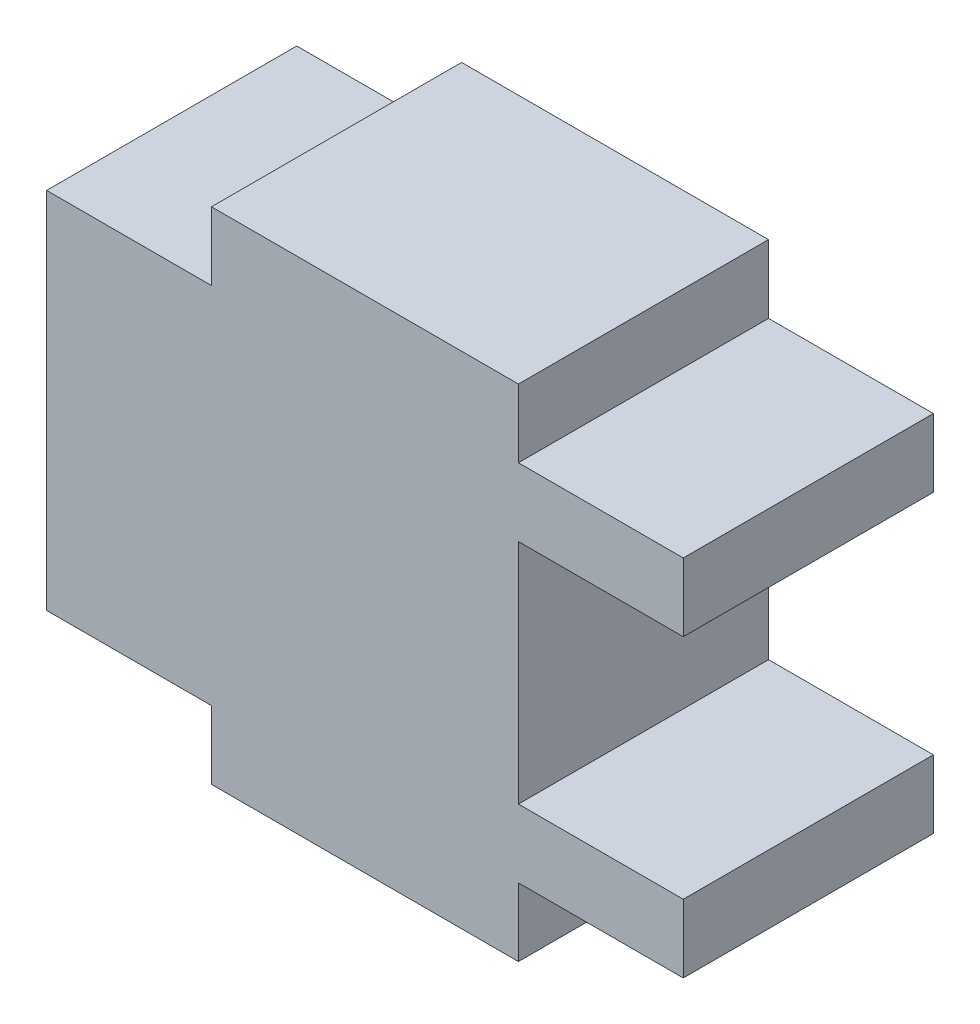
SolidWorks part; units mm, degrees
ref_plane "前视基准面" through (0, 0, 0) normal (0, 0, 1) x (1, 0, 0)
ref_plane "上视基准面" through (0, 0, 0) normal (0, 1, 0) x (1, 0, 0)
ref_plane "右视基准面" through (0, 0, 0) normal (1, 0, 0) x (0, 0, -1)
sketch "草图1" plane through (0, 0, 0) normal (0, 0, 1) x (1, 0, 0)
  line L0 (-1.4, -0.8) -> (-0.675, -0.8)
  line L1 (-0.675, -0.8) -> (-0.675, -1.1)
  line L2 (-0.675, -1.1) -> (0.675, -1.1)
  line L3 (0.675, -1.1) -> (0.675, -0.8)
  line L4 (0.675, -0.8) -> (1.4, -0.8)
  line L5 (1.4, -0.8) -> (1.4, -0.5)
  line L6 (1.4, -0.5) -> (0.675, -0.5)
  line L7 (0.675, -0.5) -> (0.675, 0.5)
  line L8 (0.675, 0.5) -> (1.4, 0.5)
  line L9 (1.4, 0.5) -> (1.4, 0.8)
  line L10 (1.4, 0.8) -> (0.675, 0.8)
  line L11 (0.675, 0.8) -> (0.675, 1.1)
  line L12 (0.675, 1.1) -> (-0.675, 1.1)
  line L13 (-0.675, 1.1) -> (-0.675, 0.8)
  line L14 (-0.675, 0.8) -> (-1.4, 0.8)
  line L15 (-1.4, 0.8) -> (-1.4, -0.8)
extrude "Component_Outline" add sketch "草图1" along normal blind 1.1 separate body
sketch3d "3D草图1"
  line L0 (0, 0, 0) -> (1, 0, 0)
  line L1 (0, 0, 0) -> (0, 1, 0)
  line L2 (0, 0, 0) -> (0, 0, 1)
  point P0 (0, 0, 0)
